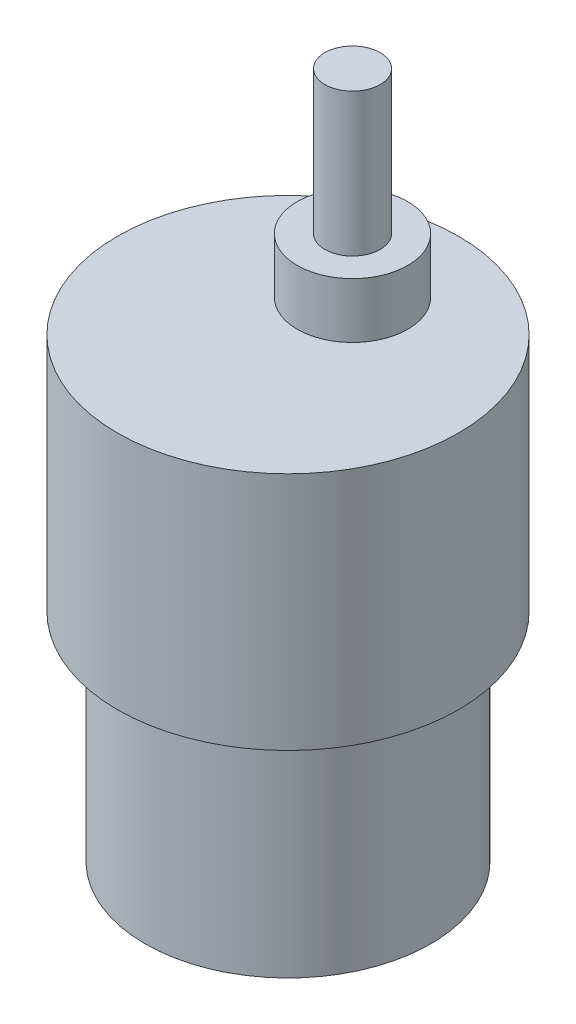
SolidWorks part; units mm, degrees
material "201 Annealed Stainless Steel (SS)"
ref_plane "Front Plane" through (0, 0, 0) normal (0, 0, 1) x (1, 0, 0)
ref_plane "Top Plane" through (0, 0, 0) normal (0, 1, 0) x (1, 0, 0)
ref_plane "Right Plane" through (0, 0, 0) normal (1, 0, 0) x (0, 0, -1)
sketch "Sketch1" plane through (0, 0, 0) normal (0, 1, 0) x (1, 0, 0)
  circle A0 centre (0, 0) radius 15.5
  dimension "D1" = 31
extrude "Boss-Extrude1" add sketch "Sketch1" along normal blind 23.5
sketch "Sketch2" plane through (0, 23.5, 0) normal (0, 1, 0) x (1, 0, 0)
  circle A1 centre (0, 0) radius 18.5
  dimension "D1" = 37
extrude "Boss-Extrude2" add sketch "Sketch2" along normal blind 26
sketch "Sketch3" plane through (0, 49.5, 0) normal (0, 1, 0) x (1, 0, 0)
  line L0 (0, 0) -> (0, 7) construction
  circle A0 centre (0, 7) radius 6
  dimension "D1" = 12
  dimension "D2" = 7
extrude "Boss-Extrude3" add sketch "Sketch3" along normal blind 6
sketch "Sketch4" plane through (0, 55.5, 0) normal (0, 1, 0) x (1, 0, 0)
  circle A0 centre (0, 7) radius 3
  dimension "D1" = 6
extrude "Boss-Extrude4" add sketch "Sketch4" along normal blind 15.5
